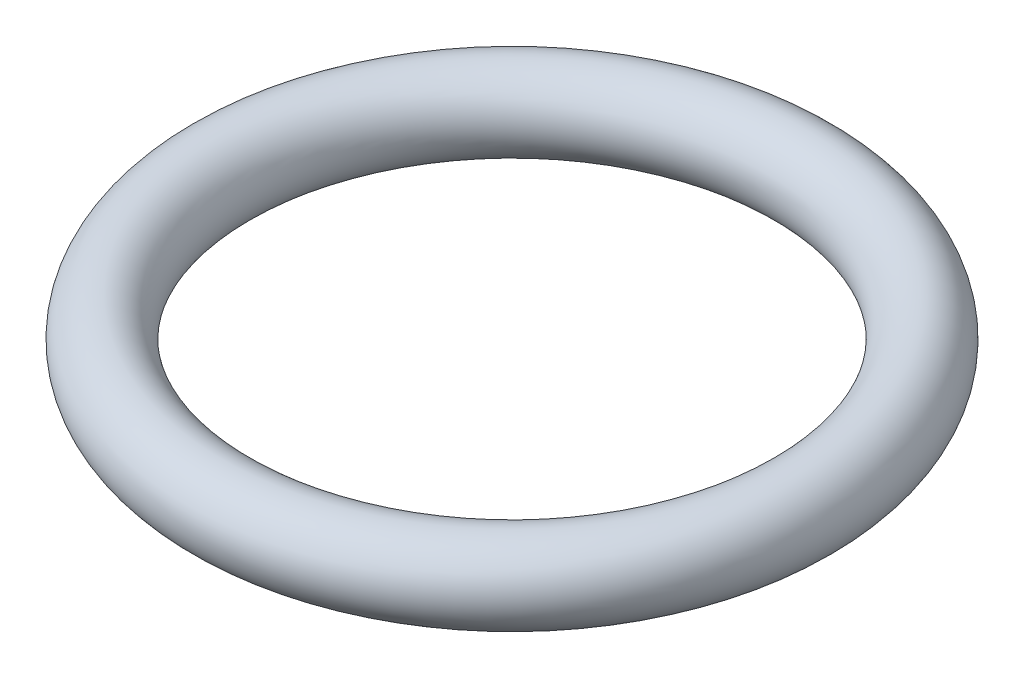
SolidWorks part; units mm, degrees
material "VITON"
ref_plane "Front Plane" through (0, 0, 0) normal (0, 0, 1) x (1, 0, 0)
ref_plane "Top Plane" through (0, 0, 0) normal (0, 1, 0) x (1, 0, 0)
ref_plane "Right Plane" through (0, 0, 0) normal (1, 0, 0) x (0, 0, -1)
sketch "MainBodyS" plane through (0, 0, 0) normal (0, 0, 1) x (1, 0, 0)
  line L0 (0, 0) -> (5.5, 0) construction
  line L1 (0, 0) -> (0, -1) construction
  circle A0 centre (5.5, 0) radius 0.75
  point P3 (6.25, 0)
  point P6 (-6.25, 0)
  point P7 (-4.75, 0)
  point P8 (4.75, 0)
  dimension "Dia" = 1.5
  dimension "RefRevolve" = 1
  dimension "RevolveDia" = 11
  dimension "OD" = 12.5
  dimension "ID" = 9.5
revolve "MAIN BODY" add sketch "MainBodyS" angle 360 about L1
